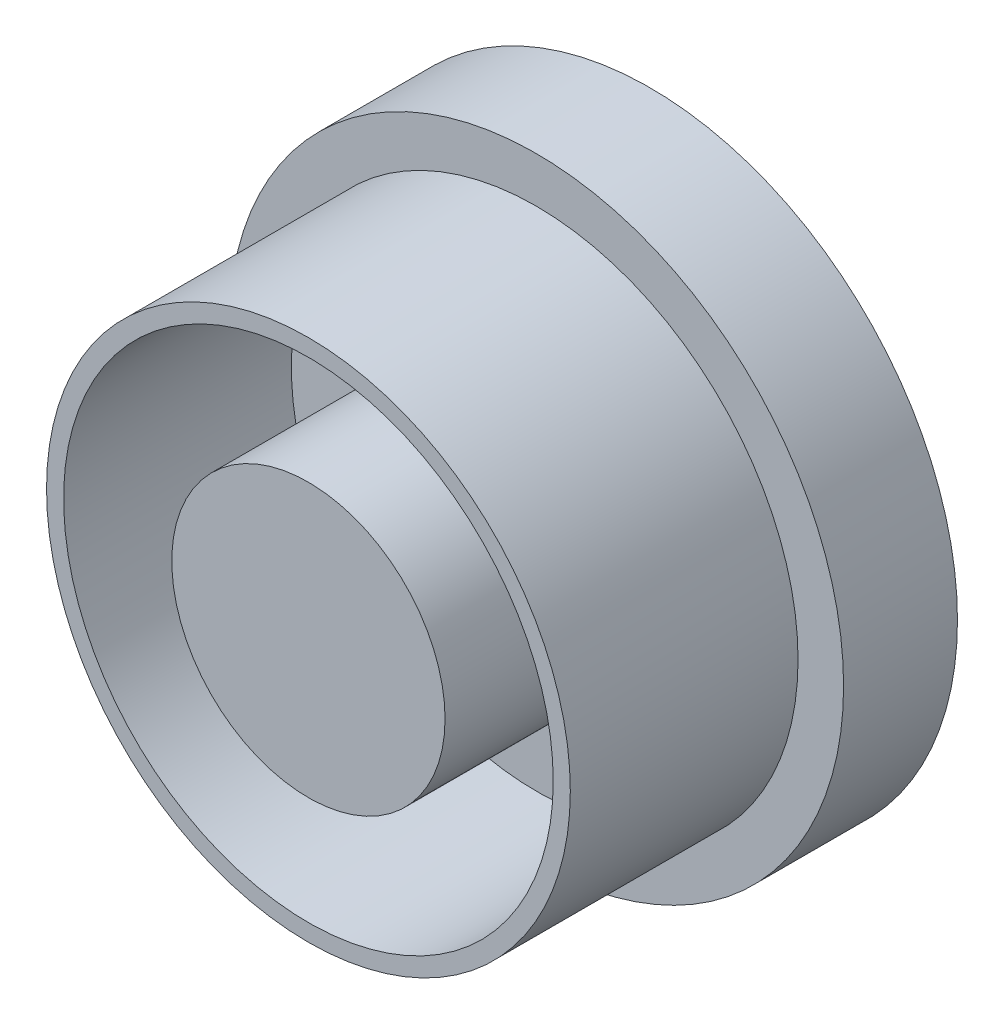
SolidWorks part; units mm, degrees
ref_plane "Front Plane" through (0, 0, 0) normal (0, 0, 1) x (1, 0, 0)
ref_plane "Top Plane" through (0, 0, 0) normal (0, 1, 0) x (1, 0, 0)
ref_plane "Right Plane" through (0, 0, 0) normal (1, 0, 0) x (0, 0, -1)
sketch "Sketch1" plane through (0, 0, 0) normal (0, 0, 1) x (1, 0, 0)
  circle A0 centre (0, 0) radius 13.5
extrude "Boss-Extrude1" add sketch "Sketch1" along normal blind 5
sketch "Sketch2" plane through (0, 0, 5) normal (0, 0, 1) x (1, 0, 0)
  circle A0 centre (0, 0) radius 11.5
  circle A1 centre (0, 0) radius 10.75
extrude "Boss-Extrude2" add sketch "Sketch2" along normal blind 10
sketch "Sketch3" plane through (0, 0, 5) normal (0, 0, 1) x (1, 0, 0)
  circle A0 centre (0, 0) radius 6
extrude "Boss-Extrude3" add sketch "Sketch3" along normal blind 10
